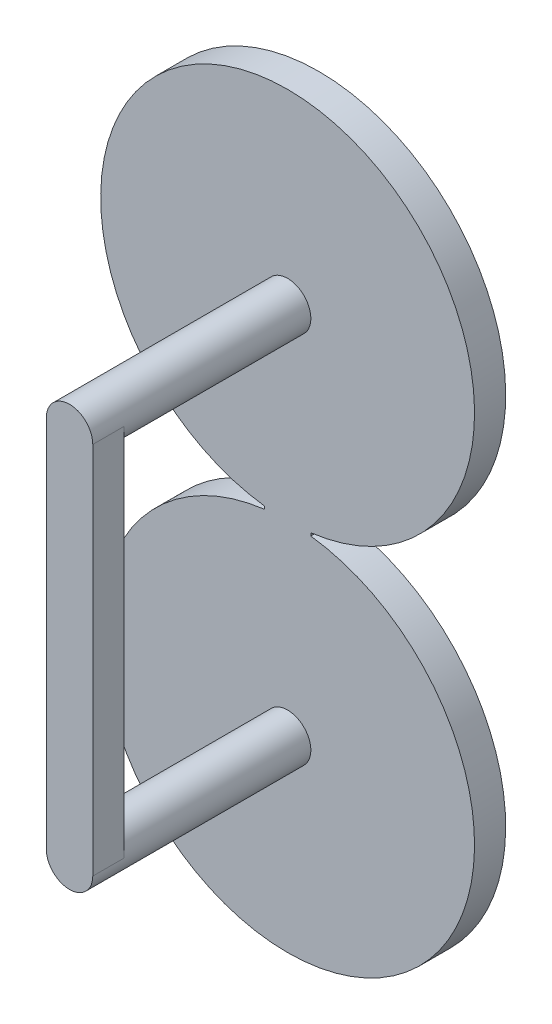
SolidWorks part; units mm, degrees
ref_plane "前视基准面" through (0, 0, 0) normal (0, 0, 1) x (1, 0, 0)
ref_plane "上视基准面" through (0, 0, 0) normal (0, 1, 0) x (1, 0, 0)
ref_plane "右视基准面" through (0, 0, 0) normal (1, 0, 0) x (0, 0, -1)
sketch "草图1" plane through (0, 0, 0) normal (0, 0, 1) x (1, 0, 0)
  circle A0 centre (0, 0) radius 1.49
  dimension "D1" = 2.98
extrude "凸台-拉伸1" add sketch "草图1" along normal blind 4
sketch "草图2" plane through (0, 0, 0) normal (0, 0, -1) x (-1, 0, 0)
  circle A0 centre (0, 0) radius 1.49
  dimension "D1" = 2.98
extrude "凸台-拉伸2" add sketch "草图2" along normal blind 4
sketch "草图3" plane through (0, 0, 4) normal (0, 0, 1) x (1, 0, 0)
  circle A0 centre (0, 0) radius 1.49
  dimension "D1" = 2.98
extrude "凸台-拉伸3" add sketch "草图3" along normal blind 4
sketch "草图4" plane through (0, 0, 0) normal (0, 1, 0) x (1, 0, 0)
  line L0 (1.49, 4) -> (-1.49, 4) construction
  line L1 (-1.49, 4) -> (1.49, 4)
  line L2 (-1.49, 4) -> (-1.49, 6)
  line L3 (-1.49, 6) -> (1.49, 6)
  line L4 (1.49, 4) -> (1.49, 6)
  point P5 (-1.49, 4)
  point P10 (1.49, 4)
  dimension "D1" = 2
extrude "凸台-拉伸4" add sketch "草图4" along normal blind 12 and the other way up to surface other way up to face at (-1.49, 0, -4)
sketch "草图9" plane through (0, 0, -6) normal (0, 0, -1) x (-1, 0, 0)
  circle A0 centre (0, 0) radius 12
  dimension "D1" = 24
extrude "凸台-拉伸6" add sketch "草图9" against normal up to surface (2 mm away) up to face at (0, 6.3725, -4)
sketch "草图6" plane through (0, 0, 0) normal (0, 1, 0) x (1, 0, 0)
  line L1 (-1.49, -8) -> (1.49, -8)
  line L2 (-1.49, -8) -> (-1.49, -10)
  line L3 (-1.49, -10) -> (1.49, -10)
  line L4 (1.49, -8) -> (1.49, -10)
  dimension "D1" = 2
extrude "凸台-拉伸5" add sketch "草图6" along normal blind 12 and the other way up to surface other way up to face at (-1.49, 0, -4)
ref_plane "基准面4" through (0, 12, 0) normal (0, 1, 0) x (1, 0, 0)
mirror "镜向2" about plane through (0, 12, 0) normal (0, 1, 0) of bodies 105
